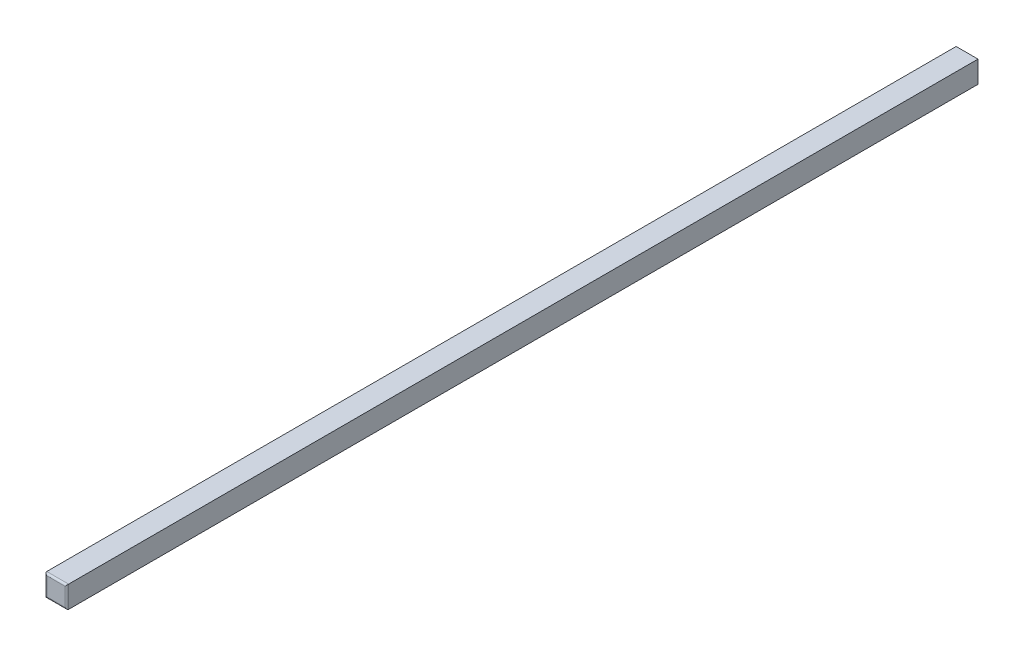
SolidWorks part; units mm, degrees
material "Plain Carbon Steel"
ref_plane "Front Plane" through (0, 0, 0) normal (0, 0, 1) x (1, 0, 0)
ref_plane "Top Plane" through (0, 0, 0) normal (0, 1, 0) x (1, 0, 0)
ref_plane "Right Plane" through (0, 0, 0) normal (1, 0, 0) x (0, 0, -1)
sketch "Sketch1" plane through (0, 0, 0) normal (0, 0, 1) x (1, 0, 0)
  line L0 (-3, 0) -> (3, 0) construction
  line L1 (0, -3) -> (0, 3) construction
  line L5 (-3, 3) -> (3, 3) construction
  line L7 (-3, 3) -> (-3, -3) construction
  line L8 (3, -3) -> (3, 3) construction
  line L13 (-3, -3) -> (3, -3) construction
  point P0 (0, 0)
  point P4 (0, 0)
  point P9 (0, 0)
  point P22 (0, 3)
  dimension "Thickness" = 6
  dimension "D1" = 6
sketch "Sketch2" plane through (0, 0, 0) normal (0, 1, 0) x (0, 0, -1)
  line L0 (125, 0) -> (-125, 0) construction
  line L2 (-125, 3) -> (125, 3) construction
  line L3 (-125, 3) -> (-125, -3) construction
  line L4 (-125, -3) -> (125, -3) construction
  line L5 (125, 3) -> (125, -3) construction
  line L6 (-125, 3) -> (125, -3) construction
  line L7 (-125, -3) -> (125, 3) construction
  point P4 (0, 0)
  point P7 (0, 0)
  point P12 (-118.1, 3)
  point P13 (118.1, 3)
  dimension "Length" = 250
  dimension "Width" = 6
  dimension "D1" = 6.9
  dimension "D2" = 6.9
sketch "Sketch3" plane through (0, 0, 0) normal (0, 0, 1) x (1, 0, 0)
  line L3 (-3, 3) -> (3, 3)
  line L17 (3, 3) -> (3, -3)
  line L18 (3, -3) -> (-3, -3)
  line L19 (-3, -3) -> (-3, 3)
extrude "Boss-Extrude1" add sketch "Sketch3" along normal mid plane 250
fillet "Fillet1" radius 0.5 4 edges at (0, 3, 125) (-3, 0, 125) (3, 0, 125) (0, -3, 125)
equation "\"D1@Boss-Extrude1\" = \"Length@Sketch2\""
equation "\"D1@Sketch1\"=\"Width@Sketch2\""
equation "\"D1@Sketch2\"=\"Width@Sketch2\"*1.15"
equation "\"D2@Sketch2\"=\"D1@Sketch2\""
